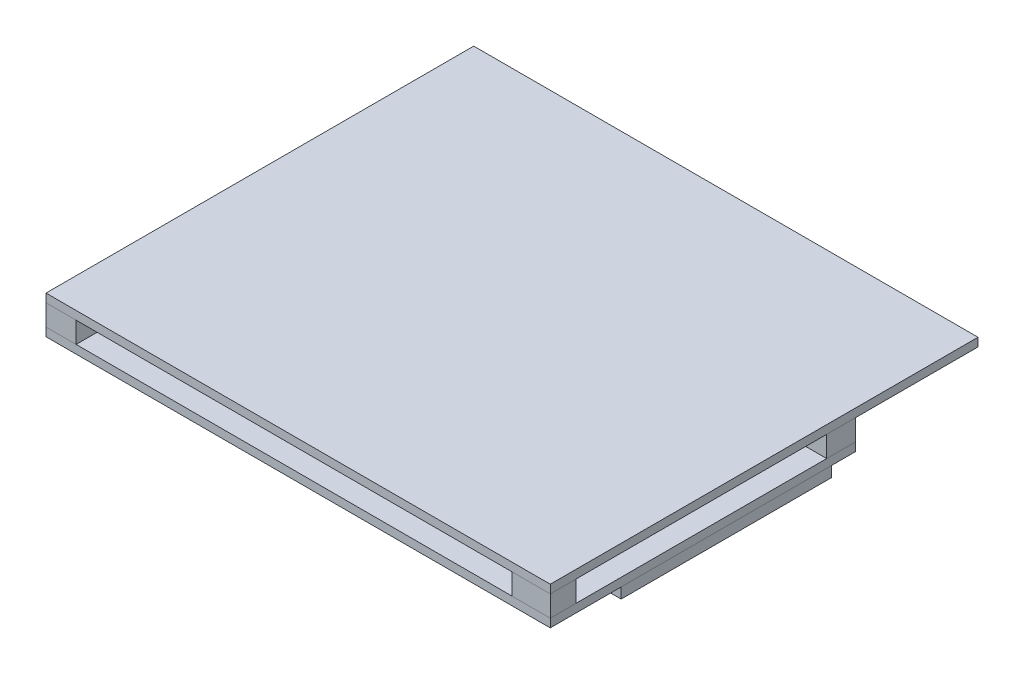
SolidWorks part; units mm, degrees
ref_plane "前视基准面" through (0, 0, 0) normal (0, 0, 1) x (1, 0, 0)
ref_plane "上视基准面" through (0, 0, 0) normal (0, 1, 0) x (1, 0, 0)
ref_plane "右视基准面" through (0, 0, 0) normal (1, 0, 0) x (0, 0, -1)
sketch "草图1" plane through (0, 0, 0) normal (0, 1, 0) x (1, 0, 0)
  line L1 (-47.9667, -29.0186) -> (47.9667, -29.0186)
  line L2 (-47.9667, -29.0186) -> (-47.9667, 29.0186)
  line L3 (-47.9667, 29.0186) -> (47.9667, 29.0186)
  line L4 (47.9667, -29.0186) -> (47.9667, 29.0186)
  line L5 (-47.9667, -29.0186) -> (47.9667, 29.0186) construction
  line L6 (-47.9667, 29.0186) -> (47.9667, -29.0186) construction
  point P0 (0, 0)
extrude "凸台-拉伸1" add sketch "草图1" along normal blind 1.6
sketch "草图2" plane through (0, 1.6, 0) normal (0, 1, 0) x (1, 0, 0)
  line L0 (-47.9667, -29.0186) -> (47.9667, -29.0186) construction
  line L1 (-47.9667, 29.0186) -> (-40.289, 29.0186)
  line L2 (-47.9667, 29.0186) -> (-47.9667, 23.5758)
  line L3 (-47.9667, 23.5758) -> (-40.289, 23.5758)
  line L4 (-40.289, 29.0186) -> (-40.289, 23.5758)
  line L5 (-42.2384, -29.0186) -> (-47.9667, -29.0186)
  line L6 (-42.2384, -29.0186) -> (-42.2384, -23.0981)
  line L7 (-42.2384, -23.0981) -> (-47.9667, -23.0981)
  line L8 (-47.9667, -29.0186) -> (-47.9667, -23.0981)
  line L9 (-47.9667, 29.0186) -> (-47.9667, -29.0186) construction
  line L11 (47.9667, 29.0186) -> (40.734, 29.0186)
  line L12 (47.9667, 29.0186) -> (47.9667, 23.5758)
  line L13 (47.9667, 23.5758) -> (40.734, 23.5758)
  line L14 (40.734, 29.0186) -> (40.734, 23.5758)
  line L15 (47.9667, -29.0186) -> (40.734, -29.0186)
  line L16 (47.9667, -29.0186) -> (47.9667, -24.1322)
  line L17 (47.9667, -24.1322) -> (40.734, -24.1322)
  line L18 (40.734, -29.0186) -> (40.734, -24.1322)
extrude "凸台-拉伸2" add sketch "草图2" along normal blind 4 separate body
ref_plane "基准面1" through (-47.9667, 1.6, -29.0186) normal (0, 0, 1) x (1, 0, 0)
sketch "草图4" plane through (0, 1.6, 0) normal (0, 1, 0) x (1, 0, 0)
  line L1 (-42.0786, 12.9215) -> (5.1653, 12.9215)
  line L2 (-42.0786, 12.9215) -> (-42.0786, -13.5675)
  line L3 (-42.0786, -13.5675) -> (5.1653, -13.5675)
  line L4 (5.1653, 12.9215) -> (5.1653, -13.5675)
extrude "凸台-拉伸3" add sketch "草图4" along normal blind 1.5
sketch "草图5" plane through (0, 0, 0) normal (0, -1, 0) x (1, 0, 0)
  line L0 (47.9667, 29.0186) -> (47.9667, -29.0186) construction
  line L1 (47.9667, -24.4663) -> (-47.9667, -24.4663)
  line L2 (47.9667, -24.4663) -> (47.9667, 15.5328)
  line L3 (47.9667, 15.5328) -> (-47.9667, 15.5328)
  line L4 (-47.9667, -24.4663) -> (-47.9667, 15.5328)
  line L5 (-47.9667, -29.0186) -> (-47.9667, 29.0186) construction
extrude "凸台-拉伸4" add sketch "草图5" along normal blind 2 separate body
sketch "草图6" plane through (0, 5.6, 0) normal (0, 1, 0) x (1, 0, 0)
  line L1 (-47.9667, -29.0186) -> (47.9695, -29.0186)
  line L2 (-47.9667, -29.0186) -> (-47.9667, 52.3577)
  line L3 (-47.9667, 52.3577) -> (47.9695, 52.3577)
  line L4 (47.9695, -29.0186) -> (47.9695, 52.3577)
extrude "凸台-拉伸5" add sketch "草图6" along normal blind 1.6
sketch "草图7" plane through (0, 5.6, 0) normal (0, -1, 0) x (1, 0, 0)
  line L1 (10.6978, -30.7497) -> (-10.6978, -30.7497)
  line L2 (10.6978, -30.7497) -> (10.6978, -49.3368)
  line L3 (10.6978, -49.3368) -> (-10.6978, -49.3368)
  line L4 (-10.6978, -30.7497) -> (-10.6978, -49.3368)
  line L5 (10.6978, -30.7497) -> (-10.6978, -49.3368) construction
  line L6 (10.6978, -49.3368) -> (-10.6978, -30.7497) construction
  point P0 (0, -40.0432)
extrude "凸台-拉伸6" add sketch "草图7" along normal blind 5
sketch "草图8" plane through (0, 0.6, 0) normal (0, -1, 0) x (1, 0, 0)
  circle A0 centre (0, -40.0955) radius 6.47
extrude "凸台-拉伸7" add sketch "草图8" along normal blind 2
